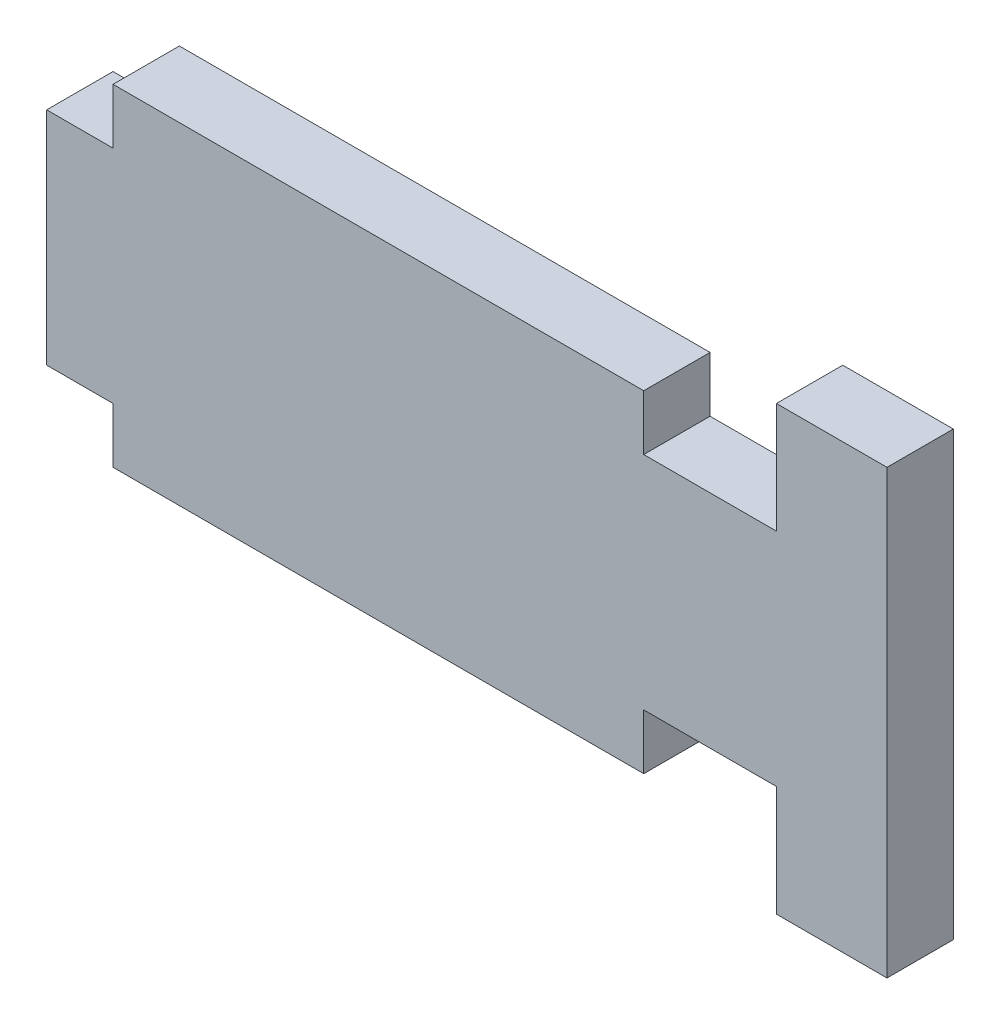
SolidWorks part; units mm, degrees
material "MDF"
ref_plane "Plano frontal" through (0, 0, 0) normal (0, 0, 1) x (1, 0, 0)
ref_plane "Plano superior" through (0, 0, 0) normal (0, 1, 0) x (1, 0, 0)
ref_plane "Plano direito" through (0, 0, 0) normal (1, 0, 0) x (0, 0, -1)
sketch "Esboço1" plane through (0, 0, 0) normal (0, 0, 1) x (1, 0, 0)
  line L0 (0, 0) -> (12, 0) construction
  line L1 (-12, -7.5) -> (12, -7.5)
  line L2 (-12, -7.5) -> (-12, 7.5)
  line L3 (-12, 7.5) -> (12, 7.5)
  line L4 (12, -7.5) -> (12, 7.5)
  line L5 (-12, -7.5) -> (12, 7.5) construction
  line L6 (-12, 7.5) -> (12, -7.5) construction
  line L11 (0, 0) -> (0, -7.5) construction
  line L12 (-15, -5) -> (-12, -5)
  line L17 (-15, -5) -> (-15, 5)
  line L18 (-15, 5) -> (-12, 5)
  line L19 (-12, -5) -> (-12, 5)
  line L20 (-15, -5) -> (-12, 5) construction
  line L21 (-15, 5) -> (-12, -5) construction
  line L26 (18, 5) -> (12, 5)
  line L27 (12, -5) -> (12, 5)
  line L28 (18, -5) -> (12, -5)
  line L29 (18, -5) -> (18, 5)
  line L30 (18, 5) -> (18, 10)
  line L31 (18, 10) -> (23, 10)
  line L32 (23, 10) -> (23, -10)
  line L33 (23, -10) -> (18, -10)
  line L34 (18, -5) -> (18, -10)
  point P0 (0, 0)
  point P6 (-13.5, 0)
  point P7 (23, 0)
  point P23 (0, 0)
  dimension "D5" = 6
  dimension "D1" = 15
  dimension "D2" = 3
  dimension "D3" = 10
  dimension "D4" = 24
  dimension "D6" = 5
  dimension "D7" = 20
extrude "Ressalto-extrusão1" add sketch "Esboço1" along normal blind 3
